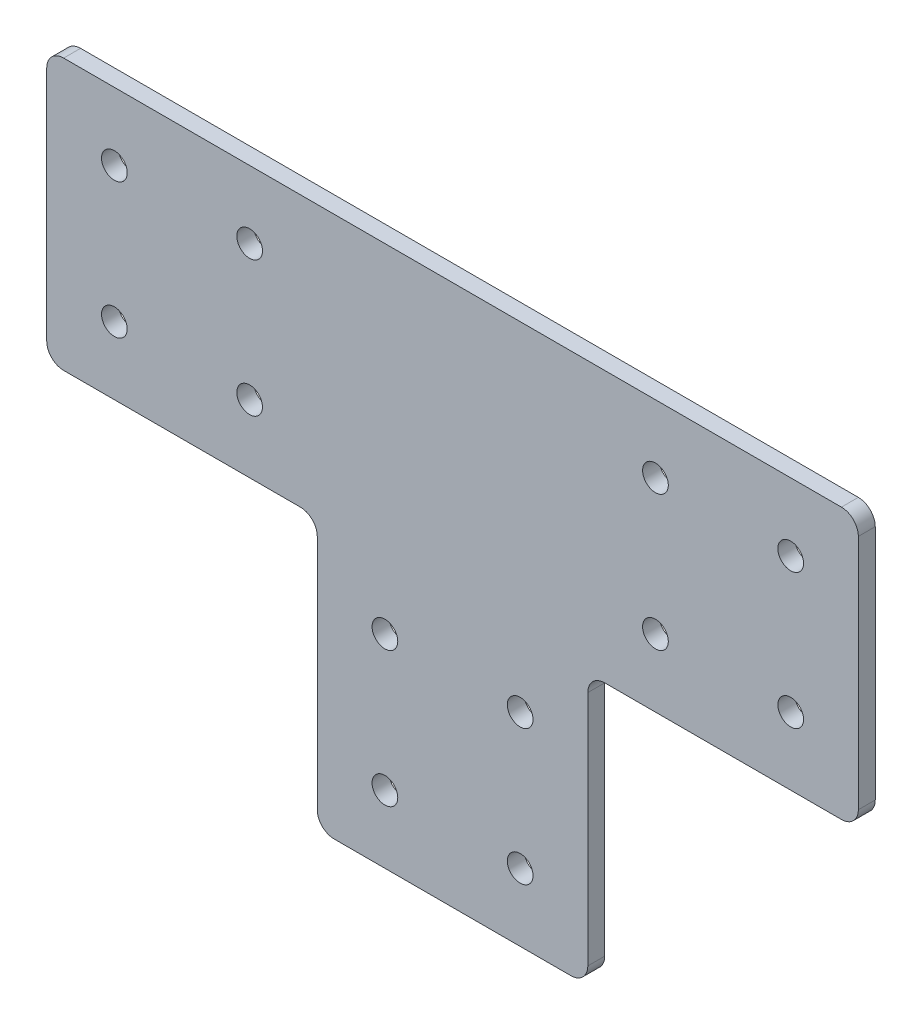
SolidWorks part; units mm, degrees
material "6061-T6 (SS)"
ref_plane "Front Plane" through (0, 0, 0) normal (0, 0, 1) x (1, 0, 0)
ref_plane "Top Plane" through (0, 0, 0) normal (0, 1, 0) x (1, 0, 0)
ref_plane "Right Plane" through (0, 0, 0) normal (1, 0, 0) x (0, 0, -1)
sketch "Sketch1" plane through (0, 0, 0) normal (0, 0, 1) x (1, 0, 0)
  line L0 (-76.2, 0) -> (76.2, 0)
  line L1 (76.2, 0) -> (76.2, -50.8)
  line L2 (76.2, -50.8) -> (25.4, -50.8)
  line L3 (25.4, -50.8) -> (25.4, -101.6)
  line L4 (25.4, -101.6) -> (-25.4, -101.6)
  line L5 (-25.4, -101.6) -> (-25.4, -50.8)
  line L6 (-25.4, -50.8) -> (-76.2, -50.8)
  line L7 (-76.2, -50.8) -> (-76.2, 0)
  line L8 (0, 0) -> (0, -50000) construction
  circle A0 centre (-63.5, -12.7) radius 2.413
  circle A1 centre (-63.5, -38.1) radius 2.413
  circle A2 centre (-38.1, -12.7) radius 2.413
  circle A3 centre (-38.1, -38.1) radius 2.413
  circle A4 centre (-12.7, -88.9) radius 2.413
  circle A5 centre (-12.7, -63.5) radius 2.413
  circle A6 centre (12.7, -88.9) radius 2.413
  circle A7 centre (12.7, -63.5) radius 2.413
  circle A8 centre (63.5, -38.1) radius 2.413
  circle A9 centre (38.1, -38.1) radius 2.413
  circle A10 centre (38.1, -12.7) radius 2.413
  circle A11 centre (63.5, -12.7) radius 2.413
  point P4 (0, 0)
  point P10 (0, -101.6)
  dimension "D5" = 4.826
  dimension "D6" = 12.7
  dimension "D7" = 25.4
  dimension "D8" = 25.4
  dimension "D9" = 25.4
  dimension "D10" = 12.7
  dimension "D11" = 12.7
  dimension "D12" = 12.7
  dimension "D1" = 50.8
  dimension "D2" = 50.8
  dimension "D3" = 50.8
  dimension "D4" = 50.8
extrude "Boss-Extrude1" add sketch "Sketch1" along normal blind 3.175
fillet "Fillet1" radius 3.175 8 edges at (25.4, -101.6, 1.5875) (-25.4, -101.6, 1.5875) (-25.4, -50.8, 1.5875) (-76.2, -50.8, 1.5875) (76.2, 0, 1.5875) (76.2, -50.8, 1.5875) (25.4, -50.8, 1.5875) (-76.2, 0, 1.5875)
